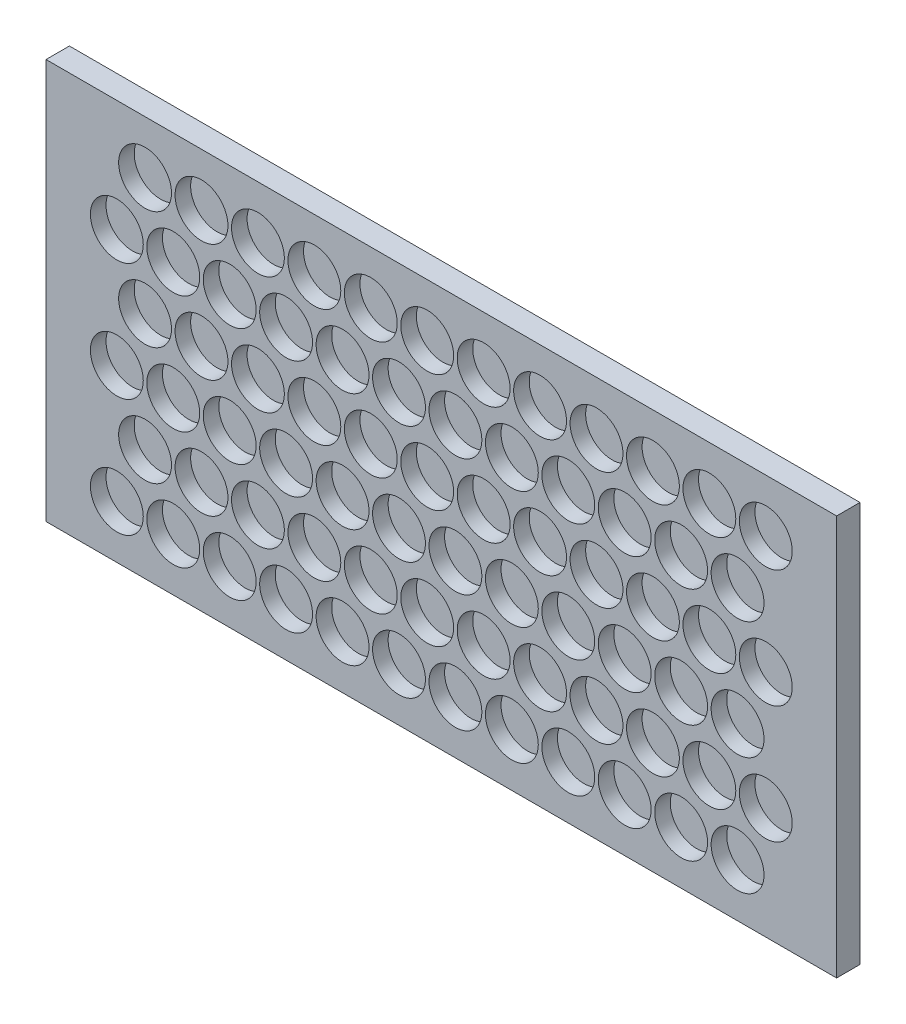
SolidWorks part; units mm, degrees
material "Custom Plastic"
ref_plane "X-Y Datum" through (0, 0, 0) normal (0, 0, 1) x (1, 0, 0)
ref_plane "X-Z Datum" through (0, 0, 0) normal (0, 1, 0) x (1, 0, 0)
ref_plane "Y-Z Datum" through (0, 0, 0) normal (1, 0, 0) x (0, 0, -1)
sketch "Sketch1" plane through (0, 0, 0) normal (0, 0, 1) x (1, 0, 0)
  line L1 (0, 0) -> (322.2286, 0)
  line L2 (0, 0) -> (0, 163.1)
  line L3 (0, 163.1) -> (322.2286, 163.1)
  line L4 (322.2286, 0) -> (322.2286, 163.1)
  dimension "D2" = 163.1
  dimension "D3" = 322.2286
extrude "Boss-Extrude1" add sketch "Sketch1" along normal blind 6.35
sketch "Sketch2" plane through (0, 0, 6.35) normal (0, 0, 1) x (1, 0, 0)
  line L1 (0, 0) -> (322.2286, 0) construction
  line L2 (316.8411, 163.1) -> (316.8411, 152.325)
  line L3 (0, 163.1) -> (322.2286, 163.1) construction
  line L10 (322.2286, 0) -> (322.2286, 163.1) construction
  line L12 (18.0875, 21.55) -> (28.8625, 21.55)
  line L13 (28.8625, 21.55) -> (28.8625, 10.775)
  line L14 (28.8625, 21.55) -> (51.8625, 21.55) construction
  line L15 (28.8625, 21.55) -> (40.3661, 45.545)
  line L16 (40.3661, 45.545) -> (63.3661, 45.545) construction
  line L18 (18.0875, 10.775) -> (304.1411, 10.775)
  line L19 (0, 0) -> (0, 163.1) construction
  line L20 (18.0875, 10.775) -> (18.0875, 152.325)
  line L21 (18.0875, 152.325) -> (304.1411, 152.325)
  line L22 (304.1411, 10.775) -> (304.1411, 152.325)
  circle A0 centre (28.8625, 21.55) radius 10.775
  circle A12 centre (51.8625, 21.55) radius 10.775
  circle A13 centre (74.8625, 21.55) radius 10.775
  circle A14 centre (97.8625, 21.55) radius 10.775
  circle A15 centre (120.8625, 21.55) radius 10.775
  circle A16 centre (143.8625, 21.55) radius 10.775
  circle A17 centre (166.8625, 21.55) radius 10.775
  circle A18 centre (189.8625, 21.55) radius 10.775
  circle A19 centre (212.8625, 21.55) radius 10.775
  circle A20 centre (235.8625, 21.55) radius 10.775
  circle A21 centre (258.8625, 21.55) radius 10.775
  circle A22 centre (281.8625, 21.55) radius 10.775
  circle A23 centre (40.3661, 45.545) radius 10.775
  circle A24 centre (63.3661, 45.545) radius 10.775
  circle A25 centre (86.3661, 45.545) radius 10.775
  circle A26 centre (109.3661, 45.545) radius 10.775
  circle A27 centre (132.3661, 45.545) radius 10.775
  circle A28 centre (155.3661, 45.545) radius 10.775
  circle A29 centre (178.3661, 45.545) radius 10.775
  circle A30 centre (201.3661, 45.545) radius 10.775
  circle A31 centre (224.3661, 45.545) radius 10.775
  circle A32 centre (247.3661, 45.545) radius 10.775
  circle A33 centre (270.3661, 45.545) radius 10.775
  circle A34 centre (293.3661, 45.545) radius 10.775
  circle A35 centre (28.8625, 69.55) radius 10.775
  circle A36 centre (51.8625, 69.55) radius 10.775
  circle A37 centre (74.8625, 69.55) radius 10.775
  circle A38 centre (97.8625, 69.55) radius 10.775
  circle A39 centre (120.8625, 69.55) radius 10.775
  circle A40 centre (143.8625, 69.55) radius 10.775
  circle A41 centre (166.8625, 69.55) radius 10.775
  circle A42 centre (189.8625, 69.55) radius 10.775
  circle A43 centre (212.8625, 69.55) radius 10.775
  circle A44 centre (235.8625, 69.55) radius 10.775
  circle A45 centre (258.8625, 69.55) radius 10.775
  circle A46 centre (281.8625, 69.55) radius 10.775
  circle A47 centre (28.8625, 117.55) radius 10.775
  circle A48 centre (51.8625, 117.55) radius 10.775
  circle A49 centre (74.8625, 117.55) radius 10.775
  circle A50 centre (97.8625, 117.55) radius 10.775
  circle A51 centre (120.8625, 117.55) radius 10.775
  circle A52 centre (143.8625, 117.55) radius 10.775
  circle A53 centre (166.8625, 117.55) radius 10.775
  circle A54 centre (189.8625, 117.55) radius 10.775
  circle A55 centre (212.8625, 117.55) radius 10.775
  circle A56 centre (235.8625, 117.55) radius 10.775
  circle A57 centre (258.8625, 117.55) radius 10.775
  circle A58 centre (281.8625, 117.55) radius 10.775
  circle A59 centre (40.3661, 93.545) radius 10.775
  circle A60 centre (63.3661, 93.545) radius 10.775
  circle A61 centre (86.3661, 93.545) radius 10.775
  circle A62 centre (109.3661, 93.545) radius 10.775
  circle A63 centre (132.3661, 93.545) radius 10.775
  circle A64 centre (155.3661, 93.545) radius 10.775
  circle A65 centre (178.3661, 93.545) radius 10.775
  circle A66 centre (201.3661, 93.545) radius 10.775
  circle A67 centre (224.3661, 93.545) radius 10.775
  circle A68 centre (247.3661, 93.545) radius 10.775
  circle A69 centre (270.3661, 93.545) radius 10.775
  circle A70 centre (293.3661, 93.545) radius 10.775
  circle A71 centre (40.3661, 141.545) radius 10.775
  circle A72 centre (63.3661, 141.545) radius 10.775
  circle A73 centre (86.3661, 141.545) radius 10.775
  circle A74 centre (109.3661, 141.545) radius 10.775
  circle A75 centre (132.3661, 141.545) radius 10.775
  circle A76 centre (155.3661, 141.545) radius 10.775
  circle A77 centre (178.3661, 141.545) radius 10.775
  circle A78 centre (201.3661, 141.545) radius 10.775
  circle A79 centre (224.3661, 141.545) radius 10.775
  circle A80 centre (247.3661, 141.545) radius 10.775
  circle A81 centre (270.3661, 141.545) radius 10.775
  circle A82 centre (293.3661, 141.545) radius 10.775
  dimension "D2" = 18.0875
  dimension "D4" = 23
  dimension "D1" = 10.775
  dimension "D5" = 12
  dimension "D3" = 23
  dimension "D9" = 10.775
  dimension "D10" = 18.0875
  dimension "D7" = 12
  dimension "D6" = 3
  dimension "D8" = 3
extrude "Cut-Extrude1" cut sketch "Sketch2" against normal through all
sketch "Sketch4" plane through (0, 0, 0) normal (0, 0, -1) x (-1, 0, 0)
  line L1 (-322.2286, 163.1) -> (0, 163.1)
  line L2 (-322.2286, 163.1) -> (-322.2286, 0)
  line L3 (-322.2286, 0) -> (0, 0)
  line L4 (0, 163.1) -> (0, 0)
extrude "Boss-Extrude3" add sketch "Sketch4" along normal blind 3.175
